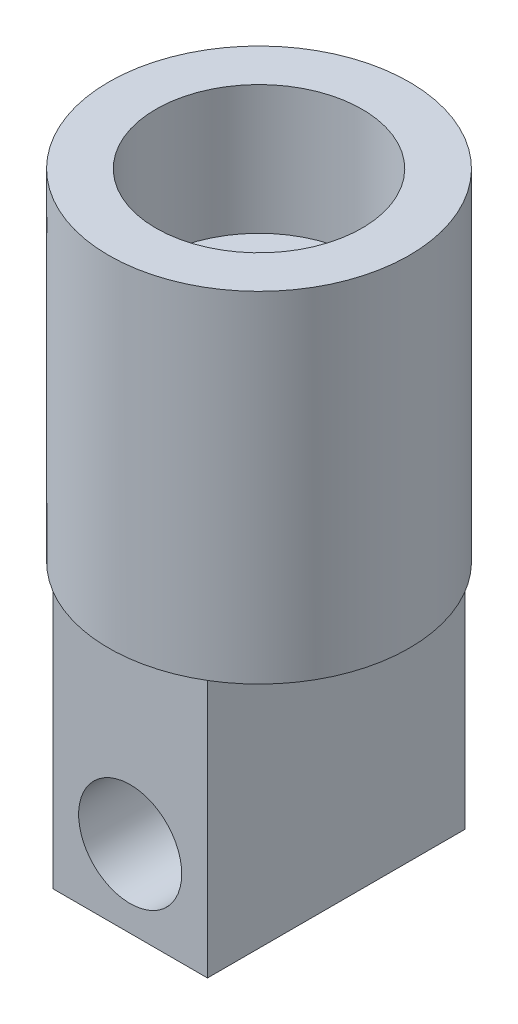
SolidWorks part; units mm, degrees
ref_plane "Plan de face" through (0, 0, 0) normal (0, 0, 1) x (1, 0, 0)
ref_plane "Plan de dessus" through (0, 0, 0) normal (0, 1, 0) x (1, 0, 0)
ref_plane "Plan de droite" through (0, 0, 0) normal (1, 0, 0) x (0, 0, -1)
sketch "Esquisse1" plane through (0, 0, 0) normal (0, 0, 1) x (1, 0, 0)
  line L0 (-308.5972, -55) -> (-278.5972, -25) construction
  line L1 (-308.5972, -55) -> (-278.5972, -55)
  line L2 (-308.5972, -55) -> (-308.5972, -5)
  line L3 (-308.5972, -5) -> (-278.5972, -5)
  line L4 (-278.5972, -55) -> (-278.5972, -5)
  circle A1 centre (-293.5972, -40) radius 10
  dimension "D1" = 30
  dimension "D2" = 45
  dimension "D3" = 50
extrude "Boss.-Extru.1" add sketch "Esquisse1" along normal blind 50
sketch "Esquisse3" plane through (0, -5, 0) normal (0, 1, 0) x (1, 0, 0)
  line L0 (-308.5972, 0) -> (-278.5972, -50) construction
  circle A0 centre (-293.5972, -25) radius 29.1548
extrude "Boss.-Extru.2" add sketch "Esquisse3" along normal blind 66
sketch "Esquisse4" plane through (0, 61, 0) normal (0, 1, 0) x (1, 0, 0)
  circle A0 centre (-293.5972, -25) radius 20
  dimension "D1" = 40
extrude "Enlèv. mat.-Extru.1" cut sketch "Esquisse4" against normal blind 25
